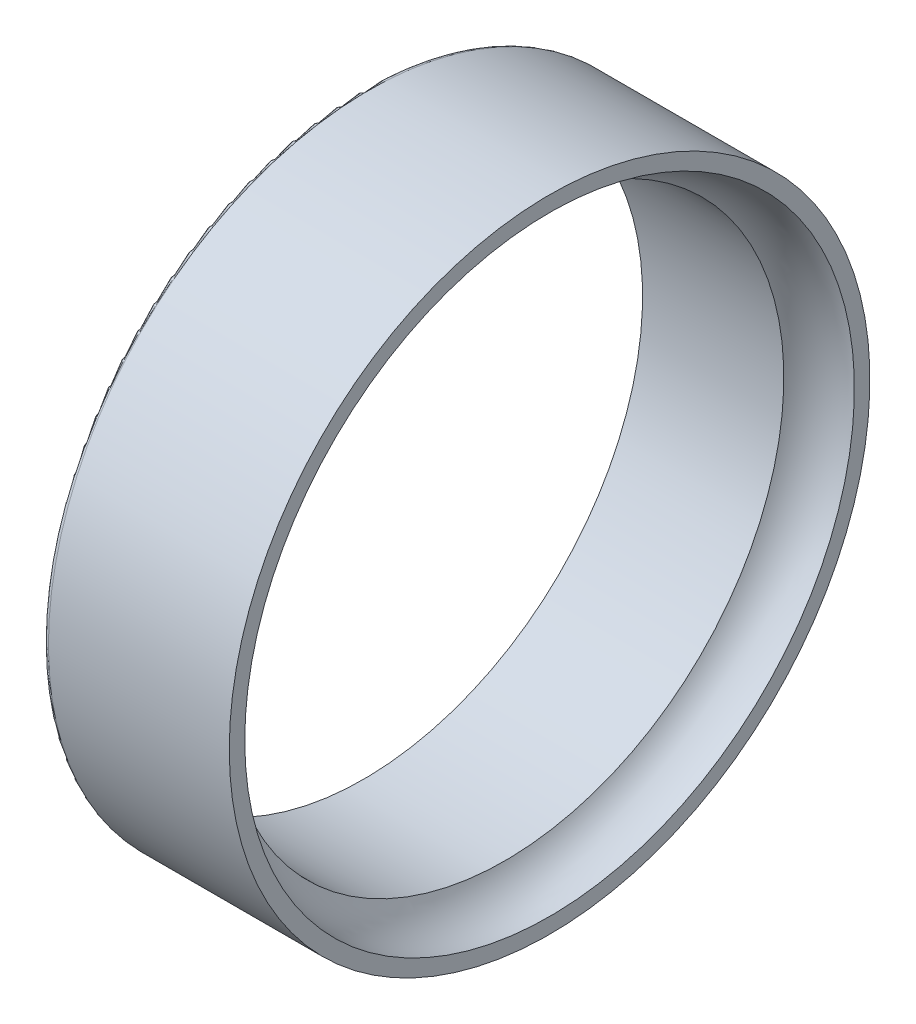
SolidWorks part; units mm, degrees
ref_plane "Plan1" through (0, 0, 0) normal (0, 0, 1) x (1, 0, 0)
ref_plane "Plan2" through (0, 0, 0) normal (0, 1, 0) x (1, 0, 0)
ref_plane "Plan3" through (0, 0, 0) normal (1, 0, 0) x (0, 0, -1)
sketch "Esquisse1" plane through (0, 0, 0) normal (0, 0, 1) x (1, 0, 0)
  line L0 (0, 27) -> (13.6699, 27)
  line L1 (0, 27) -> (0, 30.5)
  line L2 (0.5, 31) -> (18, 31)
  line L3 (18, 32.288) -> (18, 17.4195) construction
  line L4 (18, 29.5) -> (18, 31)
  line L5 (-2.8223, 0) -> (27.5582, 0) construction
  line L6 (50, 0) -> (-200, 0) construction
  arc A0 (18, 29.5) -> (13.6699, 27) centre (18, 24.5) ccw
  arc A1 (0, 30.5) -> (0.5, 31) centre (0.5, 30.5) cw
  dimension "D1" = 0.5
revolve "Base-Révolution" add sketch "Esquisse1" angle 360 about L5
